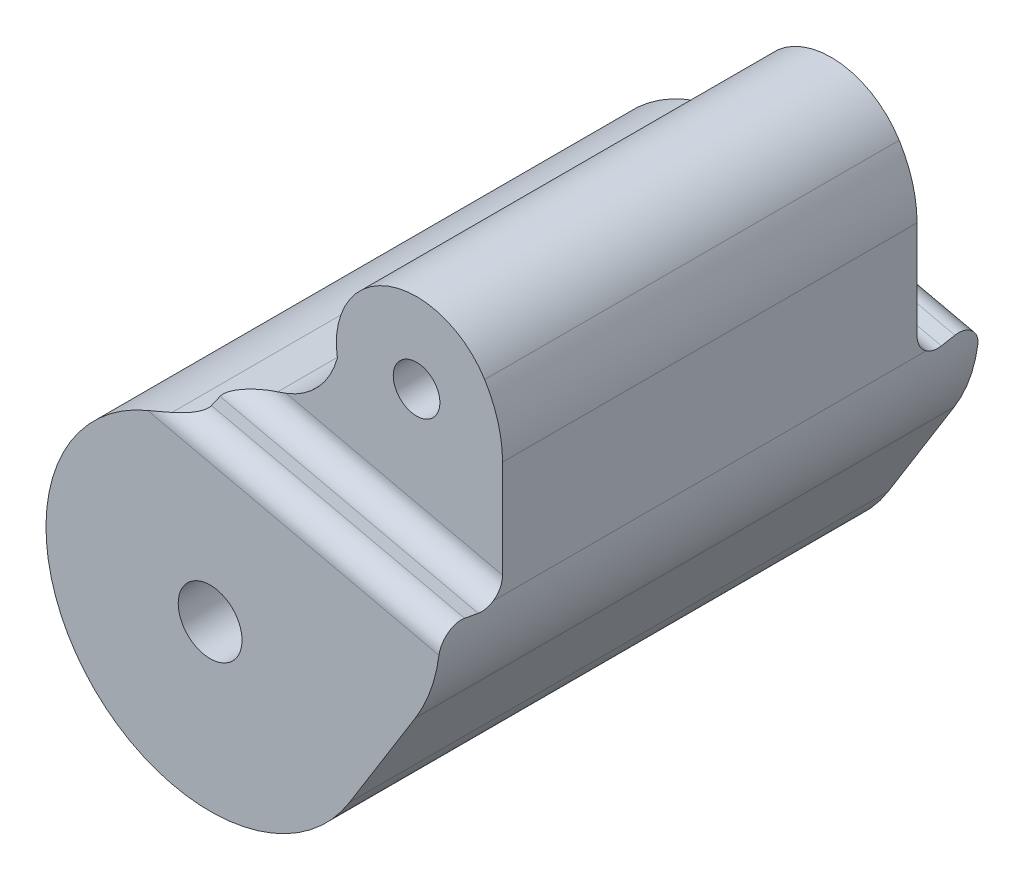
SolidWorks part; units mm, degrees
ref_plane "Front Plane" through (0, 0, 0) normal (0, 0, 1) x (1, 0, 0)
ref_plane "Top Plane" through (0, 0, 0) normal (0, 1, 0) x (1, 0, 0)
ref_plane "Right Plane" through (0, 0, 0) normal (1, 0, 0) x (0, 0, -1)
sketch "Sketch1" plane through (0, 0, 0) normal (0, 0, 1) x (1, 0, 0)
  line L0 (8, 5.57) -> (8, 0)
  line L1 (6.7954, -4.2217) -> (3.6186, -9.3352)
  line L4 (-5.1153, 2.5059) -> (-2.8302, 3.1043)
  arc A0 (0.0298, 5.9359) -> (7.1384, 8.589) centre (3.8513, 6.5464) cw
  arc A1 (7.1384, 8.589) -> (8, 5.57) centre (2.28, 5.57) cw
  arc A2 (8, 0) -> (6.7954, -4.2217) centre (0, 0) cw
  arc A3 (3.6186, -9.3352) -> (-5.1153, 2.5059) centre (-3.1089, -5.1558) cw
  arc A5 (0.0298, 5.9359) -> (-2.8302, 3.1043) centre (-3.8487, 6.9932) cw
  circle A6 centre (3.8513, 6.5464) radius 1.125
  circle A7 centre (-3.1089, -5.1558) radius 1.54
  dimension "D1" = 3.87
  dimension "D2" = 5.72
  dimension "D4" = 8
  dimension "D6" = 7.92
  dimension "D7" = 4.02
  dimension "D9" = 2.25
  dimension "D10" = 3.08
  dimension "D3" = 5.57
  dimension "D5" = 6.02
  dimension "D8" = 7.7
extrude "Boss-Extrude1" add sketch "Sketch1" along normal mid plane 26
sketch "Sketch2" plane through (0, 0, 13) normal (0, 0, 1) x (1, 0, 0)
  line L0 (8, 0) -> (8, 5.57) construction
  line L1 (8, 0.1721) -> (8, 5.57)
  line L2 (-3.782, 2.8551) -> (8, 0.1721)
  line L3 (-2.8302, 3.1043) -> (-5.1153, 2.5059) construction
  line L4 (-2.8302, 3.1043) -> (-3.782, 2.8551)
  arc A0 (7.1384, 8.589) -> (0.0298, 5.9359) centre (3.8513, 6.5464) ccw construction
  arc A1 (7.1384, 8.589) -> (0.0298, 5.9359) centre (3.8513, 6.5464) ccw
  circle A2 centre (3.8513, 6.5464) radius 1.125 construction
  arc A3 (-2.8302, 3.1043) -> (0.0298, 5.9359) centre (-3.8487, 6.9932) ccw construction
  arc A4 (8, 5.57) -> (7.1384, 8.589) centre (2.28, 5.57) ccw construction
  circle A5 centre (3.8513, 6.5464) radius 1.125
  arc A6 (-2.8302, 3.1043) -> (0.0298, 5.9359) centre (-3.8487, 6.9932) ccw
  arc A7 (8, 5.57) -> (7.1384, 8.589) centre (2.28, 5.57) ccw
  point P12 (0, 0)
  point P13 (2.4981, 10.1721)
  point P14 (-5.2811, 3.1043)
  point P15 (0, 0)
  dimension "D1" = 10
extrude "Cut-Extrude1" cut sketch "Sketch2" against normal blind 3 draft 10
mirror "Mirror1" about plane through (0, 0, 0) normal (0, 0, 1) of "Cut-Extrude1"
fillet "Fillet1" radius 1 1 edges at (2.109, 1.5136, -13)
fillet "Fillet2" radius 1 1 edges at (2.109, 1.5136, 13)
fillet "Fillet3" radius 1 1 edges at (1.5507, 1.0982, -10)
fillet "Fillet4" radius 1 1 edges at (1.5507, 1.0982, 10)
equation "\"A\"= 3.87mm"
equation "\"D1@Sketch1\"=\"A\""
equation "\"D2@Sketch1\"=\"A\"*(5.72/3.87)"
equation "\"D3@Sketch1\"=\"A\"*(5.57/3.87)"
equation "\"D4@Sketch1\"=\"A\"*(8/3.87)"
equation "\"D5@Sketch1\"=\"A\"*(6.02/3.87)"
equation "\"D6@Sketch1\"=\"A\"*(7.92/3.87)"
equation "\"D7@Sketch1\"=\"A\"*(4.02/3.87)"
equation "\"D8@Sketch1\"=\"A\"*(7.7/3.87)"
equation "\"D9@Sketch1\"=\"A\"*(2.25/3.87)"
equation "\"D10@Sketch1\"=\"A\"*(3.08/3.87)"
equation "\"D1@Boss-Extrude1\"=\"A\"*(26/3.87)"
equation "\"D1@Sketch2\"=\"A\"*(10/3.87)"
equation "\"D1@Cut-Extrude1\"=\"A\"*(3/3.87)"
